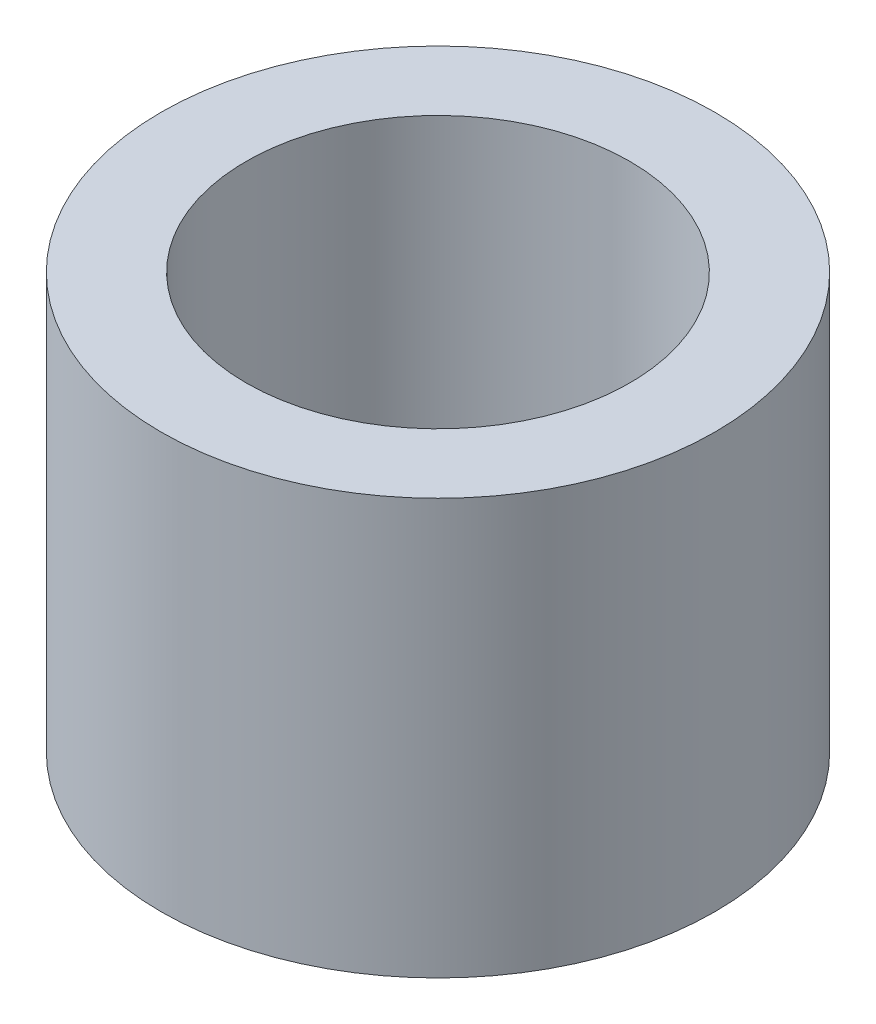
SolidWorks part; units mm, degrees
ref_plane "Plano frontal" through (0, 0, 0) normal (0, 0, 1) x (1, 0, 0)
ref_plane "Plano superior" through (0, 0, 0) normal (0, 1, 0) x (1, 0, 0)
ref_plane "Plano direito" through (0, 0, 0) normal (1, 0, 0) x (0, 0, -1)
sketch "Esboço1" plane through (0, 0, 0) normal (0, 1, 0) x (1, 0, 0)
  circle A0 centre (0, 0) radius 3.175
  circle A1 centre (0, 0) radius 2.2
  dimension "D1" = 4.4
  dimension "D2" = 6.35
extrude "Ressalto-extrusão1" add sketch "Esboço1" along normal blind 4.7625
